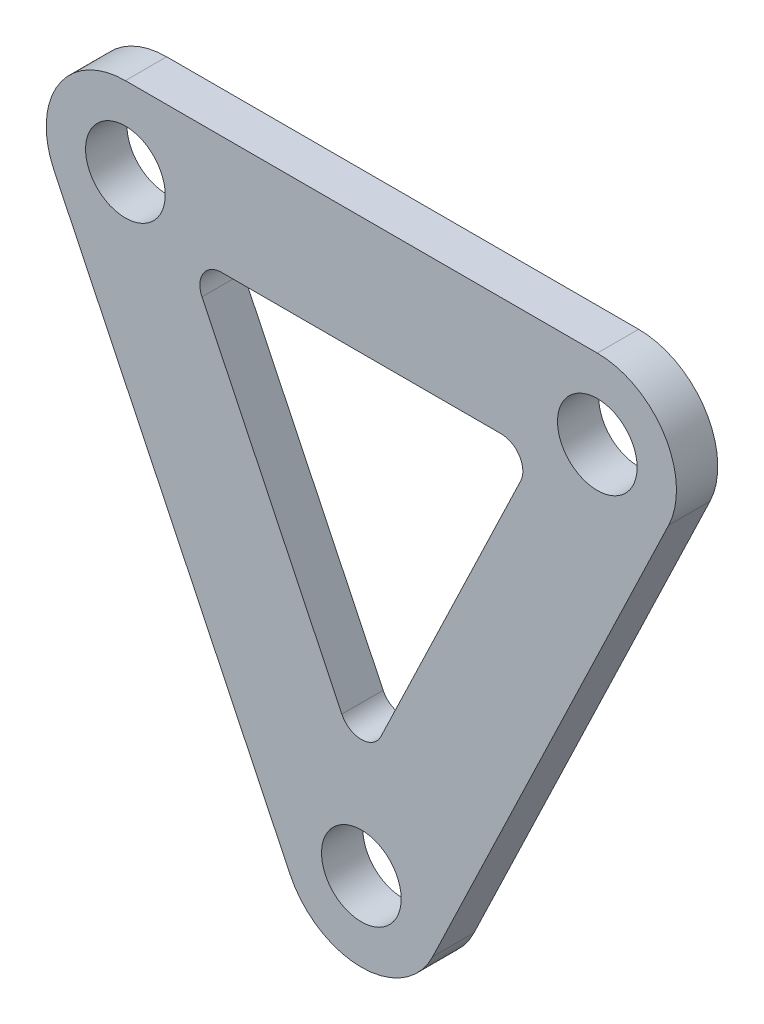
SolidWorks part; units mm, degrees
material "ABS"
ref_plane "前视基准面" through (0, 0, 0) normal (0, 0, 1) x (1, 0, 0)
ref_plane "上视基准面" through (0, 0, 0) normal (0, 1, 0) x (1, 0, 0)
ref_plane "右视基准面" through (0, 0, 0) normal (1, 0, 0) x (0, 0, -1)
other "Configuration Table"
sketch "草图1" plane through (0, 0, 0) normal (0, 0, 1) x (1, 0, 0)
  line L0 (-12, 16.525) -> (12, 16.525)
  line L1 (-12, -12.5) -> (12, -12.5) construction
  line L2 (-12, -12.5) -> (-12, 12.5) construction
  line L3 (-12, 12.5) -> (12, 12.5) construction
  line L4 (12, -12.5) -> (12, 12.5) construction
  line L5 (-12, -12.5) -> (12, 12.5) construction
  line L6 (-12, 12.5) -> (12, -12.5) construction
  line L7 (-15.6286, 10.7583) -> (-3.6286, -14.2417)
  line L8 (15.6286, 10.7583) -> (3.6286, -14.2417)
  circle A0 centre (-12, 12.5) radius 2.025
  circle A1 centre (12, 12.5) radius 2.025
  circle A2 centre (0, -12.5) radius 2.025
  arc A3 (-12, 16.525) -> (-15.6286, 10.7583) centre (-12, 12.5) ccw
  arc A4 (15.6286, 10.7583) -> (12, 16.525) centre (12, 12.5) ccw
  arc A5 (-3.6286, -14.2417) -> (3.6286, -14.2417) centre (0, -12.5) ccw
  point P0 (0, 0)
  dimension "D3" = 4.05
  dimension "D4" = 2
  dimension "D1" = 24
  dimension "D2" = 25
extrude "凸台-拉伸1" add sketch "草图1" along normal blind 2.1
sketch "草图2" plane through (0, 0, 2.1) normal (0, 0, 1) x (1, 0, 0)
  line L6 (-8.8613, 10.525) -> (0, -7.936)
  line L7 (0, -7.936) -> (8.8613, 10.525)
  line L8 (8.8613, 10.525) -> (-8.8613, 10.525)
  line L9 (-8.8613, 10.525) -> (0, -7.936)
  line L10 (0, -7.936) -> (8.8613, 10.525)
  line L11 (8.8613, 10.525) -> (-8.8613, 10.525)
  dimension "D1" = 6
extrude "切除-拉伸1" cut sketch "草图2" against normal blind 21.1
fillet "圆角1" radius 1.1 3 edges at (8.8613, 10.525, 1.05) (0, -7.936, 1.05) (-8.8613, 10.525, 1.05)
